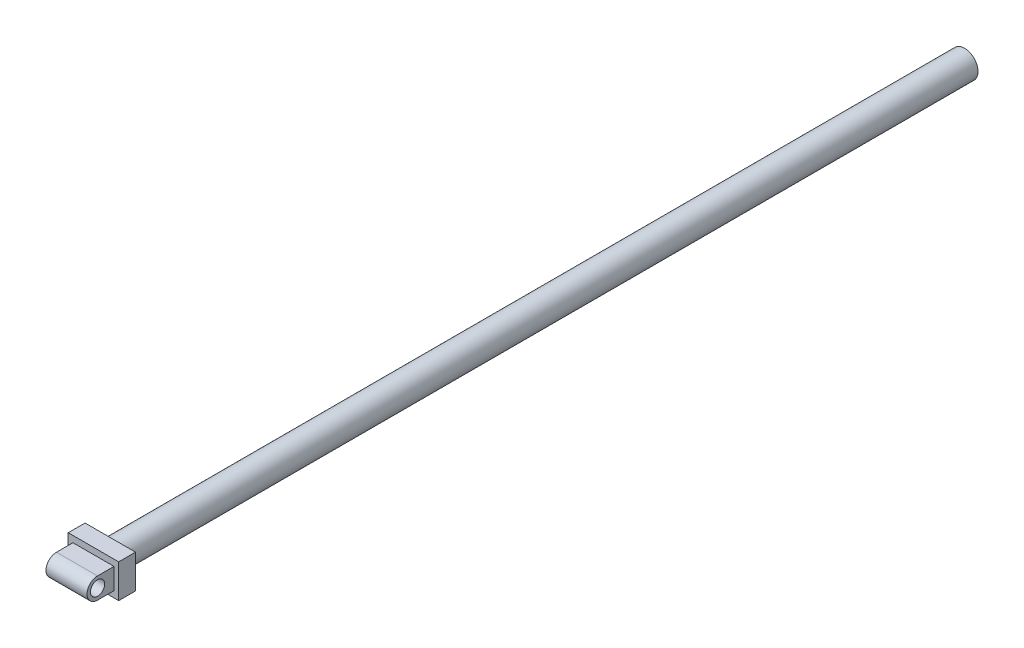
SolidWorks part; units mm, degrees
ref_plane "Front Plane" through (0, 0, 0) normal (0, 0, 1) x (1, 0, 0)
ref_plane "Top Plane" through (0, 0, 0) normal (0, 1, 0) x (1, 0, 0)
ref_plane "Right Plane" through (0, 0, 0) normal (1, 0, 0) x (0, 0, -1)
sketch "Sketch1" plane through (0, 0, 0) normal (0, 0, 1) x (1, 0, 0)
  line L1 (-6.1, -5) -> (6.1, -5)
  line L2 (-6.1, -5) -> (-6.1, 5)
  line L3 (-6.1, 5) -> (6.1, 5)
  line L4 (6.1, -5) -> (6.1, 5)
  line L5 (-6.1, -5) -> (6.1, 5) construction
  line L6 (-6.1, 5) -> (6.1, -5) construction
  point P0 (0, 0)
  dimension "D1" = 12.2
  dimension "D2" = 10
extrude "Boss-Extrude1" add sketch "Sketch1" along normal blind 10
sketch "Sketch2" plane through (-6.1, 0, 0) normal (-1, 0, 0) x (0, 0, 1)
  line L0 (4.8892, 3.125) -> (0, 3.125)
  line L1 (0, 5) -> (0, -5) construction
  line L2 (0, 3.125) -> (0, 5)
  line L3 (0, 5) -> (10, 5)
  line L4 (10, 5) -> (10, -5)
  line L5 (10, -5) -> (0, -5)
  line L6 (0, -5) -> (0, -3.125)
  line L7 (0, -3.125) -> (4.8892, -3.125)
  circle A0 centre (4.8892, 0) radius 2.125
  arc A1 (4.8892, -3.125) -> (4.8892, 3.125) centre (4.8892, 0) ccw
  dimension "D1" = 4.25
  dimension "D2" = 1
  dimension "D3" = 6.25
  dimension "D4" = 4.8892
extrude "Cut-Extrude1" cut sketch "Sketch2" against normal blind 12.2
sketch "Sketch3" plane through (0, 0, 0) normal (0, 0, -1) x (-1, 0, 0)
  line L1 (-7.5, -5) -> (7.5, -5)
  line L2 (-7.5, -5) -> (-7.5, 5)
  line L3 (-7.5, 5) -> (7.5, 5)
  line L4 (7.5, -5) -> (7.5, 5)
  line L5 (-7.5, -5) -> (7.5, 5) construction
  line L6 (-7.5, 5) -> (7.5, -5) construction
  point P0 (0, 0)
  dimension "D1" = 10
  dimension "D2" = 15
extrude "Boss-Extrude2" add sketch "Sketch3" along normal blind 5
sketch "Sketch4" plane through (0, 0, -5) normal (0, 0, -1) x (-1, 0, 0)
  circle A0 centre (0, 0) radius 4
  dimension "D1" = 8
extrude "Boss-Extrude3" add sketch "Sketch4" along normal blind 254
